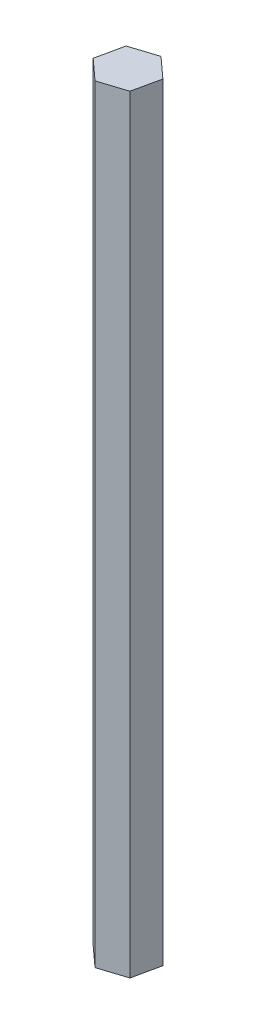
SolidWorks part; units mm, degrees
ref_plane "Front Plane" through (0, 0, 0) normal (0, 0, 1) x (1, 0, 0)
ref_plane "Top Plane" through (0, 0, 0) normal (0, 1, 0) x (1, 0, 0)
ref_plane "Right Plane" through (0, 0, 0) normal (1, 0, 0) x (0, 0, -1)
sketch "Sketch2" plane through (0, 0, 0) normal (0, 1, 0) x (1, 0, 0)
  line L1 (2.1373, -1.9404) -> (2.7491, 0.8807)
  line L2 (2.7491, 0.8807) -> (0.6118, 2.8212)
  line L3 (0.6118, 2.8212) -> (-2.1373, 1.9404)
  line L4 (-2.1373, 1.9404) -> (-2.7491, -0.8807)
  line L5 (-2.7491, -0.8807) -> (-0.6118, -2.8212)
  line L6 (-0.6118, -2.8212) -> (2.1373, -1.9404)
  circle A0 centre (0, 0) radius 2.5 construction
extrude "Boss-Extrude1" add sketch "Sketch2" along normal blind 127
sketch "Sketch3" plane through (0, 0, 0) normal (0, -1, 0) x (1, 0, 0)
  line L1 (-13.2192, 9.8568) -> (6.9753, 9.8568)
  line L2 (-13.2192, 9.8568) -> (-13.2192, -8.314)
  line L3 (-13.2192, -8.314) -> (6.9753, -8.314)
  line L4 (6.9753, 9.8568) -> (6.9753, -8.314)
extrude "Cut-Extrude1" cut sketch "Sketch3" against normal blind 38.1
sketch "Sketch4" plane through (0, 38.1, 0) normal (0, -1, 0) x (1, 0, 0)
  line L1 (0.6118, -2.8212) -> (2.7491, -0.8807)
  line L2 (2.7491, -0.8807) -> (2.1373, 1.9404)
  line L3 (2.1373, 1.9404) -> (-0.6118, 2.8212)
  line L4 (-0.6118, 2.8212) -> (-2.7491, 0.8807)
  line L5 (-2.7491, 0.8807) -> (-2.1373, -1.9404)
  line L6 (-2.1373, -1.9404) -> (0.6118, -2.8212)
  circle A0 centre (0, 0) radius 2.5 construction
extrude "Boss-Extrude2" add sketch "Sketch4" along normal blind 2.54
sketch "Sketch5" plane through (0, 35.56, 0) normal (0, -1, 0) x (1, 0, 0)
  line L1 (-18.607, 10.1377) -> (15.9105, 10.1377)
  line L2 (-18.607, 10.1377) -> (-18.607, -12.2028)
  line L3 (-18.607, -12.2028) -> (15.9105, -12.2028)
  line L4 (15.9105, 10.1377) -> (15.9105, -12.2028)
extrude "Cut-Extrude2" cut sketch "Sketch5" against normal blind 50
sketch "Sketch7" plane through (0, 85.56, 0) normal (0, -1, 0) x (1, 0, 0)
  line L1 (0.6118, -2.8212) -> (2.7491, -0.8807)
  line L2 (2.7491, -0.8807) -> (2.1373, 1.9404)
  line L3 (2.1373, 1.9404) -> (-0.6118, 2.8212)
  line L4 (-0.6118, 2.8212) -> (-2.7491, 0.8807)
  line L5 (-2.7491, 0.8807) -> (-2.1373, -1.9404)
  line L6 (-2.1373, -1.9404) -> (0.6118, -2.8212)
  circle A0 centre (0, 0) radius 2.5 construction
extrude "Boss-Extrude3" add sketch "Sketch7" along normal blind 25
sketch "Sketch8" plane through (0, 60.56, 0) normal (0, -1, 0) x (1, 0, 0)
  line L1 (0.6118, -2.8212) -> (2.7491, -0.8807)
  line L2 (2.7491, -0.8807) -> (2.1373, 1.9404)
  line L3 (2.1373, 1.9404) -> (-0.6118, 2.8212)
  line L4 (-0.6118, 2.8212) -> (-2.7491, 0.8807)
  line L5 (-2.7491, 0.8807) -> (-2.1373, -1.9404)
  line L6 (-2.1373, -1.9404) -> (0.6118, -2.8212)
  circle A0 centre (0, 0) radius 2.5 construction
extrude "Boss-Extrude4" add sketch "Sketch8" along normal blind 13.5
